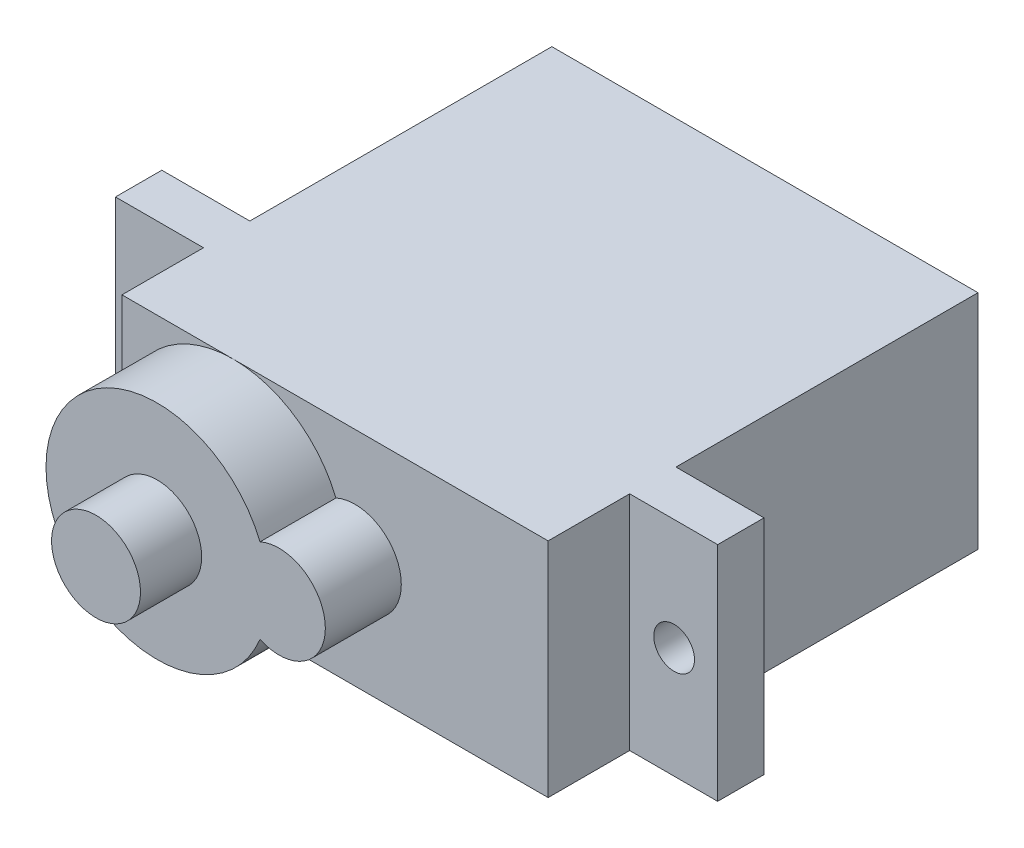
SolidWorks part; units mm, degrees
ref_plane "前视基准面" through (0, 0, 0) normal (0, 0, 1) x (1, 0, 0)
ref_plane "上视基准面" through (0, 0, 0) normal (0, 1, 0) x (1, 0, 0)
ref_plane "右视基准面" through (0, 0, 0) normal (1, 0, 0) x (0, 0, -1)
sketch "草图1" plane through (0, 0, 0) normal (0, 0, 1) x (1, 0, 0)
  line L1 (-11.5, 6) -> (11.5, 6)
  line L2 (-11.5, 6) -> (-11.5, -6)
  line L3 (-11.5, -6) -> (11.5, -6)
  line L4 (11.5, 6) -> (11.5, -6)
  line L5 (-11.5, 6) -> (11.5, -6) construction
  line L6 (-11.5, -6) -> (11.5, 6) construction
  point P0 (0, 0)
  dimension "D1" = 23
  dimension "D2" = 12
extrude "凸台-拉伸1" add sketch "草图1" along normal blind 16.3
sketch "草图2" plane through (0, 0, 16.3) normal (0, 0, 1) x (1, 0, 0)
  line L1 (-16.25, 6) -> (16.25, 6)
  line L2 (-16.25, 6) -> (-16.25, -6)
  line L3 (-16.25, -6) -> (16.25, -6)
  line L4 (16.25, 6) -> (16.25, -6)
  line L5 (-16.25, 6) -> (16.25, -6) construction
  line L6 (-16.25, -6) -> (16.25, 6) construction
  circle A0 centre (-13.9, 0) radius 1.1
  circle A1 centre (13.9, 0) radius 1.1
  point P0 (0, 0)
  point P12 (-12.7054, 5.9912)
  point P13 (16.25, -0.3247)
  dimension "D2" = 2.2
  dimension "D3" = 2.2
  dimension "D6" = 6
  dimension "D8" = 6
  dimension "D1" = 32.5
  dimension "D4" = 27.8
  dimension "D5" = 2.35
  dimension "D7" = 6
extrude "凸台-拉伸2" add sketch "草图2" along normal blind 2.5
sketch "草图3" plane through (0, 0, 18.8) normal (0, 0, 1) x (1, 0, 0)
  line L0 (-16.25, -6) -> (16.25, -6) construction
  line L1 (-11.5, 6) -> (11.5, 6)
  line L2 (-11.5, 6) -> (-11.5, -6)
  line L3 (-11.5, -6) -> (11.5, -6)
  line L4 (11.5, 6) -> (11.5, -6)
  line L5 (-11.5, 6) -> (11.5, -6) construction
  line L6 (-11.5, -6) -> (11.5, 6) construction
  point P0 (0, 0)
  dimension "D1" = 23
extrude "凸台-拉伸3" add sketch "草图3" along normal blind 4.4
sketch "草图4" plane through (0, 0, 23.2) normal (0, 0, 1) x (1, 0, 0)
  line L0 (-11.5, 6) -> (-11.5, -6) construction
  line L1 (-11.5, -6) -> (11.5, -6) construction
  arc A0 (0.05, 2.2798) -> (0.05, -2.2798) centre (-5.5, 0) ccw
  arc A1 (0.05, -2.2798) -> (0.05, 2.2798) centre (1.0758, 0) ccw
  dimension "D1" = 12
  dimension "D2" = 5
  dimension "6" = 6
  dimension "D3" = 6
extrude "凸台-拉伸4" add sketch "草图4" along normal blind 4.1
sketch "草图5" plane through (0, 0, 27.3) normal (0, 0, 1) x (1, 0, 0)
  circle A0 centre (-5.5, 0) radius 2.4
  dimension "D1" = 4.8
extrude "凸台-拉伸5" add sketch "草图5" along normal blind 3.3
